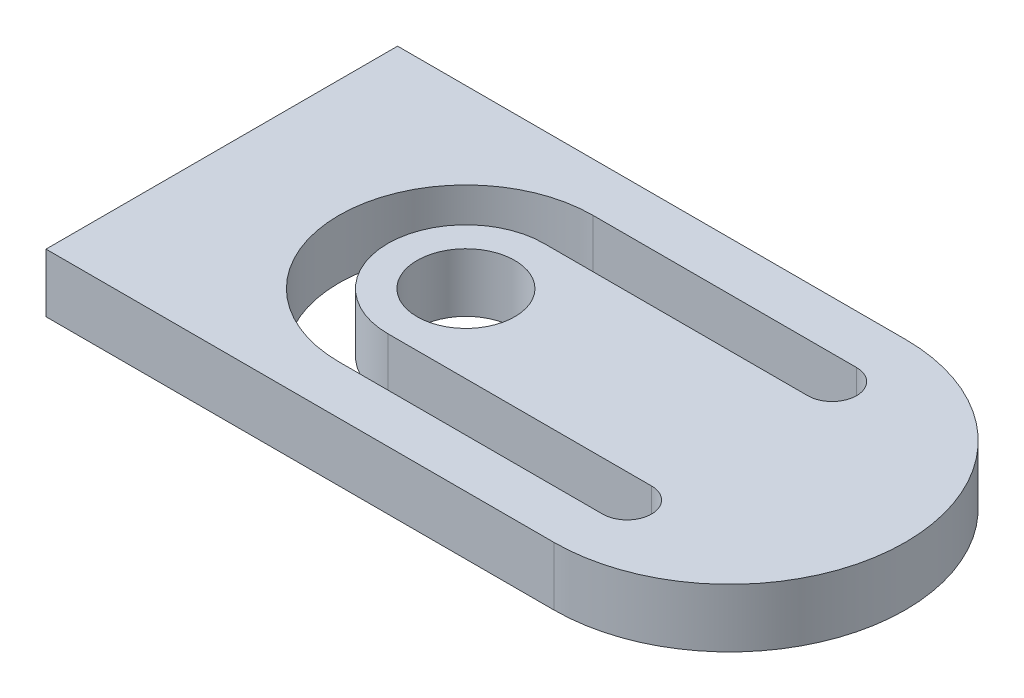
SolidWorks part; units mm, degrees
ref_plane "Front Plane" through (0, 0, 0) normal (0, 0, 1) x (1, 0, 0)
ref_plane "Top Plane" through (0, 0, 0) normal (0, 1, 0) x (1, 0, 0)
ref_plane "Right Plane" through (0, 0, 0) normal (1, 0, 0) x (0, 0, -1)
sketch "Sketch1" plane through (0, 0, 0) normal (0, 1, 0) x (1, 0, 0)
  line L1 (-19.356, 9) -> (6.644, 9)
  line L2 (-19.356, 9) -> (-19.356, -9)
  line L3 (-19.356, -9) -> (6.644, -9)
  line L10 (-6.856, -6.5) -> (6.644, -6.5)
  line L11 (-6.856, -4) -> (6.644, -4)
  line L12 (-6.856, 4) -> (6.644, 4)
  line L13 (-6.856, 6.5) -> (6.644, 6.5)
  circle A0 centre (-6.856, 0) radius 2.5
  arc A1 (6.644, 9) -> (6.644, -9) centre (6.644, 0) cw
  arc A6 (6.644, 6.5) -> (6.644, 4) centre (6.644, 5.25) cw
  arc A7 (6.644, -4) -> (6.644, -6.5) centre (6.644, -5.25) cw
  arc A8 (-6.856, 4) -> (-6.856, -4) centre (-6.856, 0) ccw
  arc A9 (-6.856, 6.5) -> (-6.856, -6.5) centre (-6.856, 0) ccw
  point P0 (0, 0)
  point P6 (0, 0)
  point P8 (-6.856, 0)
extrude "Boss-Extrude2" add sketch "Sketch1" along normal blind 3
